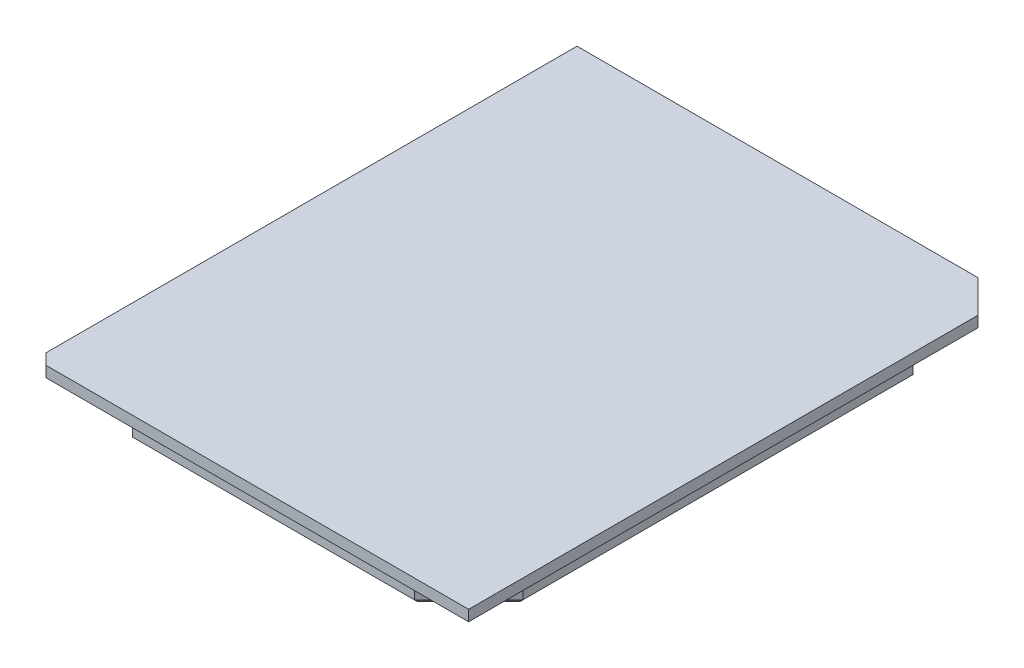
SolidWorks part; units mm, degrees
ref_plane "Front Plane" through (0, 0, 0) normal (0, 0, 1) x (1, 0, 0)
ref_plane "Top Plane" through (0, 0, 0) normal (0, 1, 0) x (1, 0, 0)
ref_plane "Right Plane" through (0, 0, 0) normal (1, 0, 0) x (0, 0, -1)
sketch "Sketch1" plane through (0, 0, 0) normal (0, 1, 0) x (1, 0, 0)
  line L1 (-40, 50) -> (40, 50)
  line L2 (-40, 50) -> (-40, -50)
  line L3 (-40, -50) -> (40, -50)
  line L4 (40, 50) -> (40, -50)
  line L5 (-40, 50) -> (40, -50) construction
  line L6 (-40, -50) -> (40, 50) construction
  point P0 (0, 0)
  dimension "D1" = 80
  dimension "D2" = 100
extrude "Boss-Extrude1" add sketch "Sketch1" along normal blind 2
chamfer "Chamfer1" distance 2 angle 45 1 edges at (-40, 1, 50)
chamfer "Chamfer2" distance 6 angle 45 1 edges at (40, 1, -50)
sketch "Sketch3" plane through (0, 0, 0) normal (0, -1, 0) x (1, 0, 0)
  line L0 (26, 46) -> (36, 36)
  line L1 (-26, -46) -> (26, -46)
  line L2 (-36, -36) -> (-36, 36)
  line L3 (-26, 46) -> (26, 46)
  line L4 (36, -36) -> (36, 36)
  line L5 (-36, -46) -> (36, 46) construction
  line L6 (-36, 46) -> (36, -46) construction
  line L7 (-36, 36) -> (-26, 46)
  line L8 (-36, -36) -> (-26, -46)
  line L9 (26, -46) -> (36, -36)
  line L10 (25.1716, 44) -> (34, 35.1716)
  line L11 (34, -35.1716) -> (34, 35.1716)
  line L12 (25.1716, -44) -> (34, -35.1716)
  line L13 (-25.1716, -44) -> (25.1716, -44)
  line L14 (-34, -35.1716) -> (-25.1716, -44)
  line L15 (-34, -35.1716) -> (-34, 35.1716)
  line L16 (-34, 35.1716) -> (-25.1716, 44)
  line L17 (-25.1716, 44) -> (25.1716, 44)
  point P0 (0, 0)
  dimension "D1" = 72
  dimension "71" = 92
  dimension "D3" = 2
extrude "Boss-Extrude2" add sketch "Sketch3" along normal blind 6.5
chamfer "Chamfer3" distance 1 angle 45 8 edges at (0, -6.5, 46) (31, -6.5, 41) (36, -6.5, 0) (31, -6.5, -41) (0, -6.5, -46) (-31, -6.5, -41) (-36, -6.5, 0) (-31, -6.5, 41)
chamfer "Chamfer4" distance 1 angle 45 8 edges at (31, 0, -41) (36, 0, 0) (31, 0, 41) (0, 0, 46) (-31, 0, 41) (-36, 0, 0) (0, 0, -46) (-31, 0, -41)
fillet "Fillet1" radius 2 8 edges at (34, 0, 0) (29.5858, 0, -39.5858) (0, 0, -44) (-29.5858, 0, -39.5858) (-34, 0, 0) (-29.5858, 0, 39.5858) (0, 0, 44) (29.5858, 0, 39.5858)
